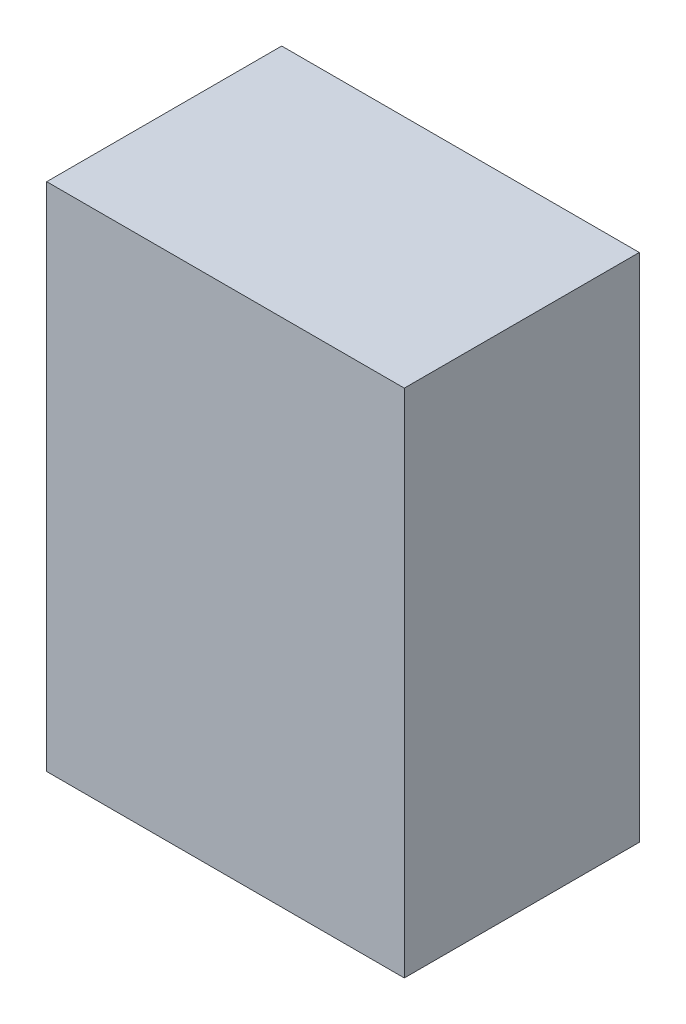
SolidWorks part; units mm, degrees
ref_plane "正面" through (0, 0, 0) normal (0, 0, 1) x (1, 0, 0)
ref_plane "平面" through (0, 0, 0) normal (0, 1, 0) x (1, 0, 0)
ref_plane "右側面" through (0, 0, 0) normal (1, 0, 0) x (0, 0, -1)
sketch "ｽｹｯﾁ1" plane through (0, 0, 0) normal (0, 0, 1) x (1, 0, 0)
  line L1 (-17.5, 25) -> (17.5, 25)
  line L2 (-17.5, 25) -> (-17.5, -25)
  line L3 (-17.5, -25) -> (17.5, -25)
  line L4 (17.5, 25) -> (17.5, -25)
  line L5 (-17.5, 25) -> (17.5, -25) construction
  line L6 (-17.5, -25) -> (17.5, 25) construction
  point P0 (0, 0)
  dimension "D1" = 50
  dimension "D2" = 35
extrude "ﾎﾞｽ - 押し出し1" add sketch "ｽｹｯﾁ1" along normal blind 23
